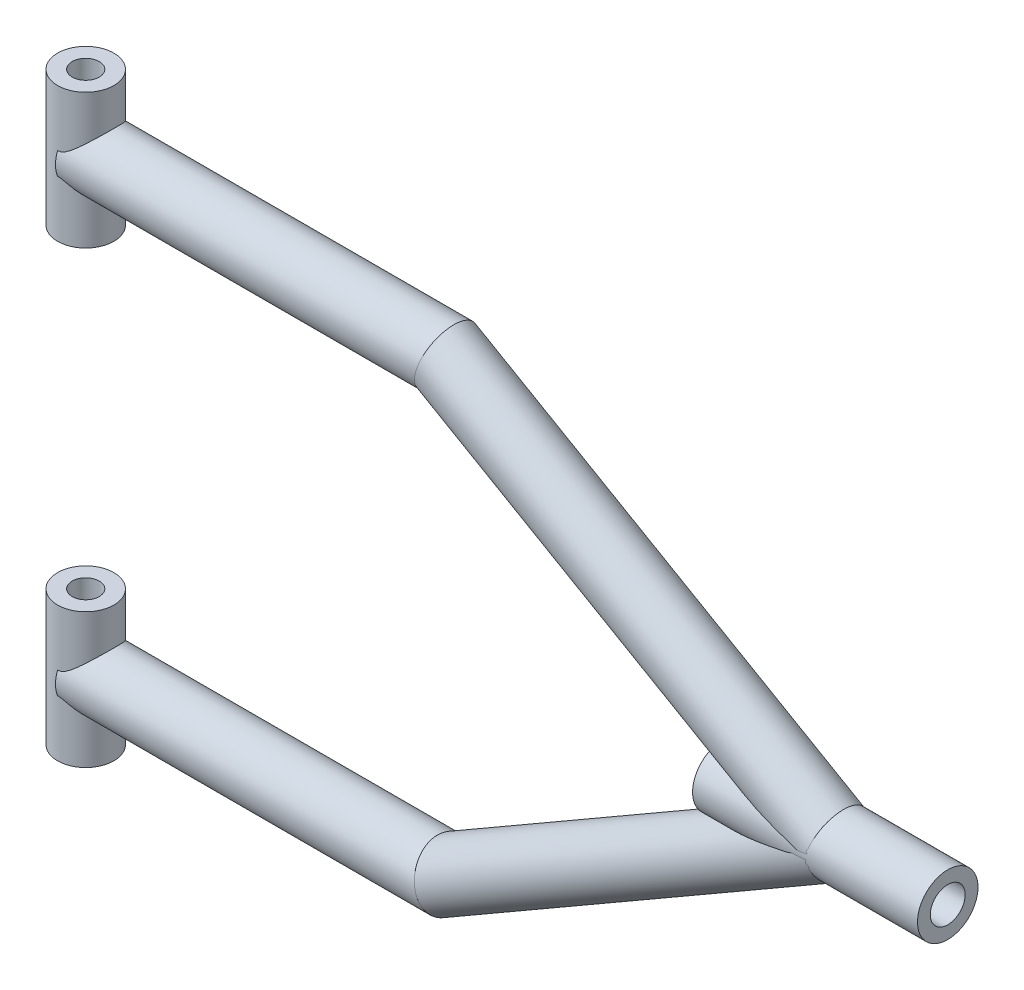
SolidWorks part; units mm, degrees
ref_plane "Front Plane" through (0, 0, 0) normal (0, 0, 1) x (1, 0, 0)
ref_plane "Top Plane" through (0, 0, 0) normal (0, 1, 0) x (1, 0, 0)
ref_plane "Right Plane" through (0, 0, 0) normal (1, 0, 0) x (0, 0, -1)
sketch "Sketch1" plane through (0, 0, 0) normal (0, 0, 1) x (1, 0, 0)
  line L0 (0, 100) -> (0, -100) construction
  line L1 (0, 100) -> (160, 100)
  line L2 (160, 100) -> (333.2051, 0)
  line L3 (333.2051, 0) -> (160, -100)
  line L4 (160, -100) -> (0, -100)
  line L5 (333.2051, 0) -> (151.4153, 0) construction
  point P4 (0, 0)
  dimension "D1" = 200
  dimension "D2" = 160
  dimension "D3" = 160
  dimension "D4" = 200
  dimension "D5" = 200
  dimension "D6" = 333.2051
  dimension "D7" = 333.2051
other "Pipe 26.9 X 3.2(1)"
ref_plane "Plane1" through (160, -100, 0) normal (-1, 0, 0) x (0, -1, 0)
sketch "Sketch11" plane through (160, -100, 0) normal (-1, 0, 0) x (0, -1, 0)
  circle A0 centre (0, 0) radius 10.45
  circle A1 centre (0, 0) radius 13.45
  point P3 (0, 13.45)
  point P5 (-13.45, 0)
  point P6 (0, -13.45)
  point P7 (13.45, 0)
  point P8 (0, 0)
  dimension "Out_dia" = 26.9
  dimension "D1" = 3
ref_plane "Plane3" through (0, -100, 0) normal (0, 1, 0) x (1, 0, 0)
sketch "Sketch13" plane through (0, -100, 0) normal (0, 1, 0) x (1, 0, 0)
  circle A0 centre (0, 0) radius 12.5
  circle A1 centre (0, 0) radius 6
  dimension "D1" = 25
  dimension "D2" = 12
extrude "Boss-Extrude1" add sketch "Sketch13" along normal mid plane 60 separate body
ref_plane "Plane4" through (0, 100, 0) normal (0, 1, 0) x (1, 0, 0)
sketch "Sketch14" plane through (0, 100, 0) normal (0, 1, 0) x (1, 0, 0)
  circle A0 centre (0, 0) radius 12.5
  circle A1 centre (0, 0) radius 6
  dimension "D1" = 25
  dimension "D2" = 12
extrude "Boss-Extrude2" add sketch "Sketch14" along normal mid plane 60 separate body
ref_plane "Plane5" through (333.2051, 0, 0) normal (1, 0, 0) x (0, 0, -1)
sketch "Sketch15" plane through (333.2051, 0, 0) normal (1, 0, 0) x (0, 0, -1)
  circle A0 centre (0, 0) radius 13.45
  circle A1 centre (0, 0) radius 7.75
  dimension "D1" = 26.9
  dimension "D2" = 15.5
extrude "Boss-Extrude3" add sketch "Sketch15" along normal mid plane 100 separate body
sketch "Sketch18" plane through (0, -130, 0) normal (0, -1, 0) x (1, 0, 0)
  circle A0 centre (0, 0) radius 6 construction
  circle A1 centre (0, 0) radius 6
extrude "Cut-Extrude1" cut sketch "Sketch18" against normal through all both and the other way through all
sketch "Sketch20" plane through (383.2051, 0, 0) normal (1, 0, 0) x (0, 0, -1)
  circle A0 centre (0, 0) radius 7.75 construction
  circle A3 centre (0, 0) radius 7.75
extrude "Cut-Extrude3" cut sketch "Sketch20" against normal through all both and the other way through all
